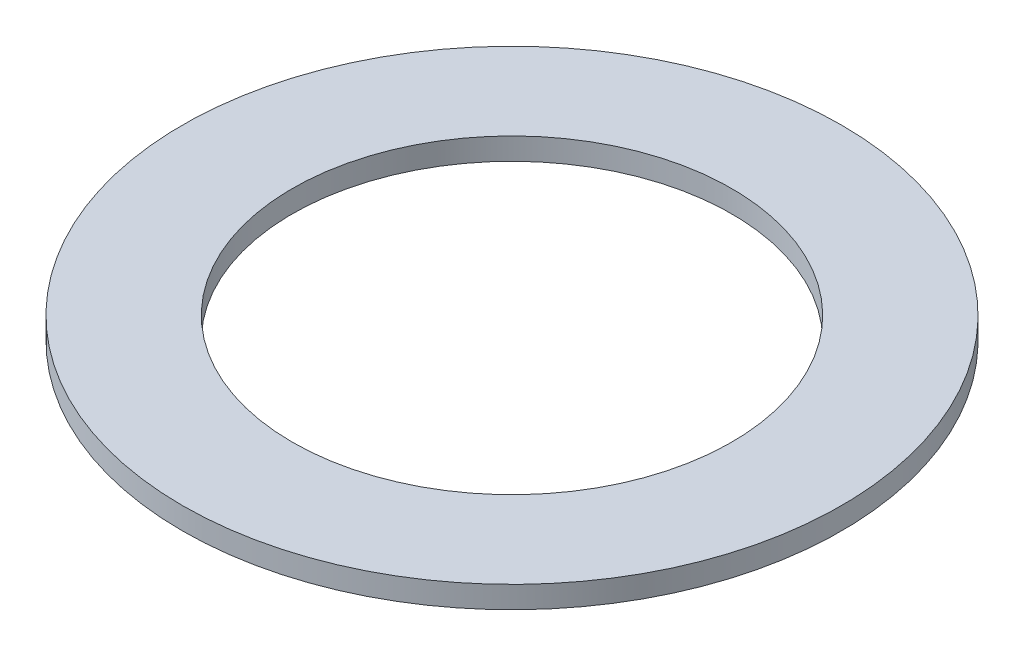
SolidWorks part; units mm, degrees
ref_plane "Front Plane" through (0, 0, 0) normal (0, 0, 1) x (1, 0, 0)
ref_plane "Top Plane" through (0, 0, 0) normal (0, 1, 0) x (1, 0, 0)
ref_plane "Right Plane" through (0, 0, 0) normal (1, 0, 0) x (0, 0, -1)
sketch "Sketch1" plane through (0, 0, 0) normal (0, 1, 0) x (1, 0, 0)
  circle A0 centre (0, 0) radius 75
  circle A1 centre (0, 0) radius 50
  dimension "D1" = 100
  dimension "D2" = 150
extrude "Boss-Extrude1" add sketch "Sketch1" along normal blind 5
